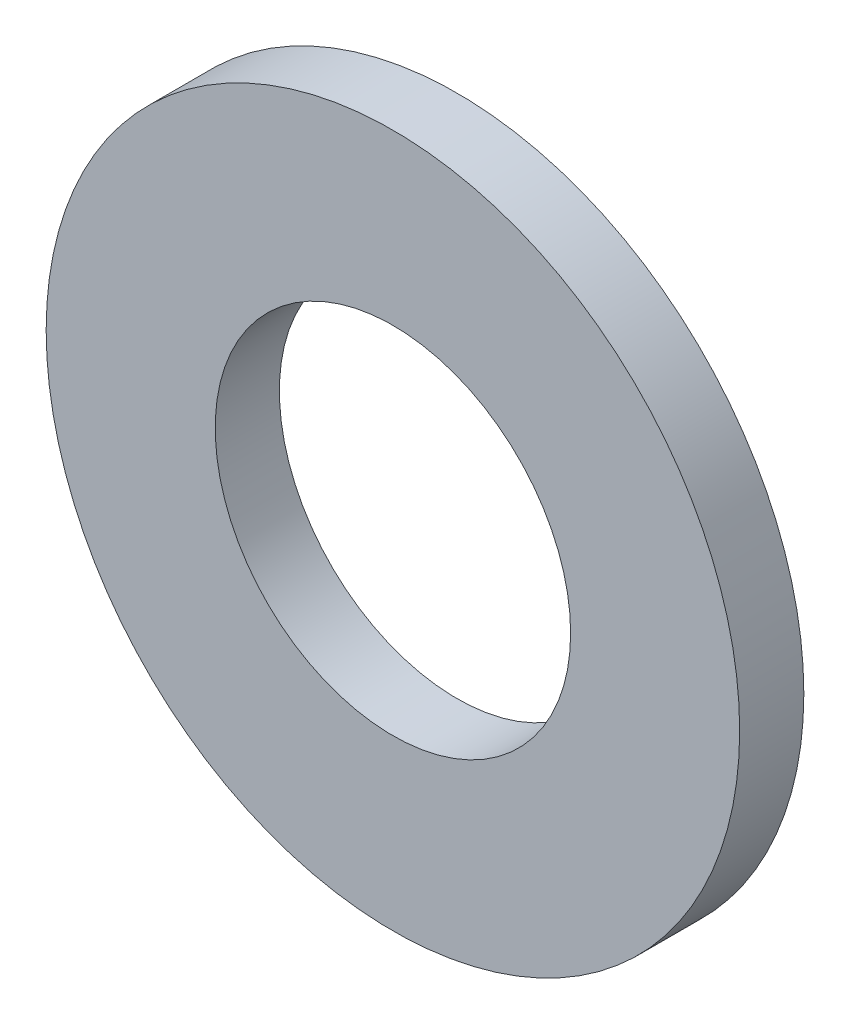
SolidWorks part; units mm, degrees
ref_plane "Front Plane" through (0, 0, 0) normal (0, 0, 1) x (1, 0, 0)
ref_plane "Top Plane" through (0, 0, 0) normal (0, 1, 0) x (1, 0, 0)
ref_plane "Right Plane" through (0, 0, 0) normal (1, 0, 0) x (0, 0, -1)
sketch "Sketch1" plane through (0, 0, 0) normal (0, 0, 1) x (1, 0, 0)
  circle A0 centre (0, 0) radius 13.0175
  circle A1 centre (0, 0) radius 25.4
  dimension "D1" = 26.035
  dimension "D2" = 50.8
extrude "Boss-Extrude1" add sketch "Sketch1" along normal blind 4.699
